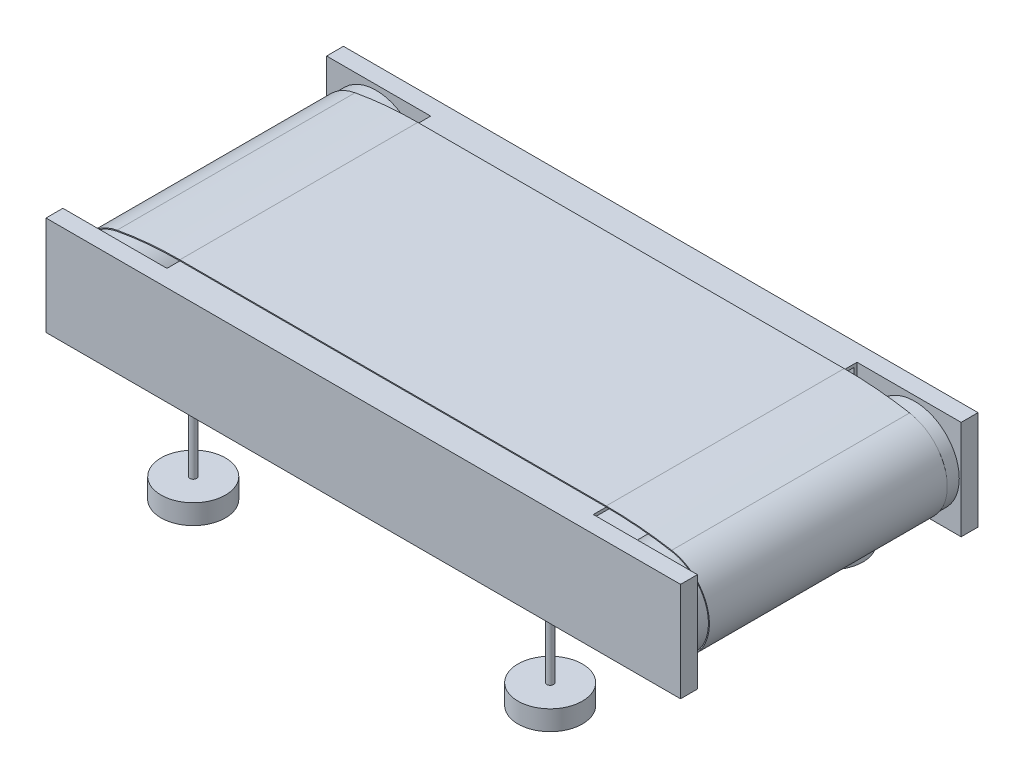
SolidWorks part; units mm, degrees
ref_plane "Alzado" through (0, 0, 0) normal (0, 0, 1) x (1, 0, 0)
ref_plane "Planta" through (0, 0, 0) normal (0, 1, 0) x (1, 0, 0)
ref_plane "Vista lateral" through (0, 0, 0) normal (1, 0, 0) x (0, 0, -1)
sketch "Croquis1" plane through (0, 0, 0) normal (0, 0, 1) x (1, 0, 0)
  line L1 (0, 0) -> (640, 0)
  line L2 (0, 0) -> (0, 100)
  line L3 (0, 100) -> (640, 100)
  line L4 (640, 0) -> (640, 100)
  dimension "D1" = 640
  dimension "D2" = 100
extrude "Saliente-Extruir1" add sketch "Croquis1" along normal mid plane 300
sketch "Croquis2" plane through (0, 100, 0) normal (0, 1, 0) x (1, 0, 0)
  line L5 (0, -150) -> (0, 150) construction
  line L6 (0, 133) -> (105, 133)
  line L7 (0, 133) -> (0, -133)
  line L8 (0, -133) -> (105, -133)
  line L9 (105, 133) -> (105, -133)
  line L10 (640, 150) -> (0, 150) construction
  line L11 (640, -150) -> (0, -150) construction
  line L12 (320, 150) -> (320, -238.7911) construction
  line L13 (535, 133) -> (535, -133)
  line L14 (640, -133) -> (535, -133)
  line L15 (640, 133) -> (640, -133)
  line L16 (640, 133) -> (535, 133)
  dimension "D1" = 17
  dimension "D2" = 17
  dimension "D3" = 105
extrude "Cortar-Extruir1" cut sketch "Croquis2" against normal mid plane 300
sketch "Croquis4" plane through (535, 0, 0) normal (1, 0, 0) x (0, 0, -1)
  line L8 (130, 3) -> (130, 97)
  line L9 (130, 97) -> (-130, 97)
  line L10 (-130, 97) -> (-130, 3)
  line L11 (-130, 3) -> (130, 3)
  line L12 (130, 3) -> (130, 97)
  line L13 (130, 97) -> (-130, 97)
  line L14 (-130, 97) -> (-130, 3)
  line L15 (-130, 3) -> (130, 3)
  dimension "D1" = 3
extrude "Cortar-Extruir2" cut sketch "Croquis4" against normal through all
sketch "Croquis5" plane through (0, 0, 0) normal (0, -1, 0) x (1, 0, 0)
  line L0 (0, 150) -> (0, 133) construction
  line L1 (0, -133) -> (0, -150) construction
  line L2 (0, -150) -> (640, -150) construction
  line L3 (320, -150) -> (320, -268.3789) construction
  circle A0 centre (140, 141.5) radius 3.5
  circle A1 centre (140, -141.5) radius 3.5
  circle A2 centre (500, -141.5) radius 3.5
  circle A3 centre (500, 141.5) radius 3.5
  point P6 (0, 141.5)
  point P7 (0, 0)
  point P11 (0, -141.5)
  dimension "D1" = 7
  dimension "D2" = 140
extrude "Saliente-Extruir2" add sketch "Croquis5" along normal blind 80
sketch "Croquis6" plane through (0, -80, 0) normal (0, -1, 0) x (1, 0, 0)
  line L0 (0, 0) -> (655.882, 0) construction
  line L1 (320, -124.3784) -> (320, -175.6216) construction
  line L2 (0, -150) -> (640, -150) construction
  circle A0 centre (500, 141.5) radius 32.5
  circle A1 centre (140, 141.5) radius 32.5
  circle A2 centre (140, -141.5) radius 32.5
  circle A3 centre (500, -141.5) radius 32.5
  point P10 (320, -150)
  dimension "D1" = 65
extrude "Saliente-Extruir3" add sketch "Croquis6" against normal blind 20 separate body
sketch "Croquis7" plane through (0, 0, -133) normal (0, 0, 1) x (1, 0, 0)
  line L0 (535, 100) -> (640, 100) construction
  circle A0 centre (593.1179, 50) radius 45
  circle A1 centre (50, 50) radius 45
  point P6 (0, 0)
  dimension "D1" = 90
  dimension "D2" = 50
  dimension "D3" = 593.1179
  dimension "D5" = 50
extrude "Saliente-Extruir4" add sketch "Croquis7" along normal up to surface (266 mm away) separate body up to face at (587.5, 50, 133)
sketch "Croquis9" plane through (0, 0, 150) normal (0, 0, 1) x (1, 0, 0)
  line L8 (105, 0) -> (535, 0)
  line L9 (105, 100) -> (535, 100)
  line L10 (105, 101) -> (535, 101)
  line L11 (105, -1) -> (535, -1)
  arc A0 (535, 100) -> (600.8679, 94.2792) centre (535, -282.0526) cw
  arc A1 (535, 0) -> (600.8679, 5.7208) centre (535, 382.0526) ccw
  arc A5 (105, 100) -> (41.8568, 94.2366) centre (105, -248.778) ccw
  arc A6 (41.8568, 94.2366) -> (41.8568, 5.7634) centre (50, 50) ccw
  arc A7 (600.8679, 5.7208) -> (600.8679, 94.2792) centre (593.1179, 50) ccw
  arc A8 (105, 0) -> (41.8568, 5.7634) centre (105, 348.778) cw
  arc A10 (601.0403, 4.7358) -> (601.0403, 95.2642) centre (593.1179, 50) ccw
  arc A11 (535, 101) -> (601.0403, 95.2642) centre (535, -282.0526) cw
  arc A12 (105, 101) -> (41.6757, 95.2201) centre (105, -248.778) ccw
  arc A13 (41.6757, 95.2201) -> (41.6757, 4.7799) centre (50, 50) ccw
  arc A14 (105, -1) -> (41.6757, 4.7799) centre (105, 348.778) cw
  arc A15 (535, -1) -> (601.0403, 4.7358) centre (535, 382.0526) ccw
  dimension "D1" = 382.0526
  dimension "D2" = 348.778
  dimension "D3" = 1
extrude "Saliente-Extruir6" add sketch "Croquis9" against normal blind 240 from offset 30 separate body offset against normal yes
